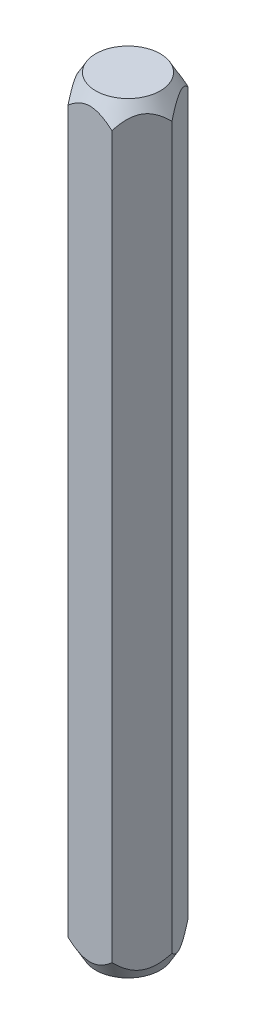
SolidWorks part; units mm, degrees
ref_plane "Front Plane" through (0, 0, 0) normal (0, 0, 1) x (1, 0, 0)
ref_plane "Top Plane" through (0, 0, 0) normal (0, 1, 0) x (1, 0, 0)
ref_plane "Right Plane" through (0, 0, 0) normal (1, 0, 0) x (0, 0, -1)
sketch "Sketch1" plane through (0, 0, 0) normal (0, 1, 0) x (1, 0, 0)
  line L0 (0, 0) -> (1.5, 0) construction
  line L7 (1.5, 0) -> (0.75, 1.299)
  line L8 (0.75, 1.299) -> (-0.75, 1.299)
  line L9 (-0.75, 1.299) -> (-1.5, 0)
  line L10 (-1.5, 0) -> (-0.75, -1.299)
  line L11 (-0.75, -1.299) -> (0.75, -1.299)
  line L12 (0.75, -1.299) -> (1.5, 0)
  circle A0 centre (0, 0) radius 1.5 construction
  dimension "D1" = 3
extrude "Boss-Extrude1" add sketch "Sketch1" along normal mid plane 26
sketch3d "3DSketch1"
  line L0 (0, -13, 0) -> (0, 13, 0)
  line L1 (1.5, 13, 0) -> (-1.5, 13, 0) construction
  line L2 (1.5, -13, 0) -> (-1.5, -13, 0) construction
  point P13 (0, -13, 0)
  point P14 (0, 13, 0)
sketch "Sketch2" plane through (0, 0, 0) normal (0, 0, 1) x (1, 0, 0)
  line L0 (1.5, 13) -> (1.5, 12.3)
  line L1 (1.5, 13) -> (1.5, -13) construction
  line L2 (1.5, 12.3) -> (1.1, 13)
  line L3 (1.1, 13) -> (1.5, 13)
  line L4 (1.5, -13) -> (1.5, -12.3)
  line L5 (1.5, -12.3) -> (1.1, -13)
  line L6 (1.1, -13) -> (1.5, -13)
  dimension "D1" = 0.7
  dimension "D2" = 0.4
revolve "Cut-Revolve1" cut sketch "Sketch2" angle 360 about L0
